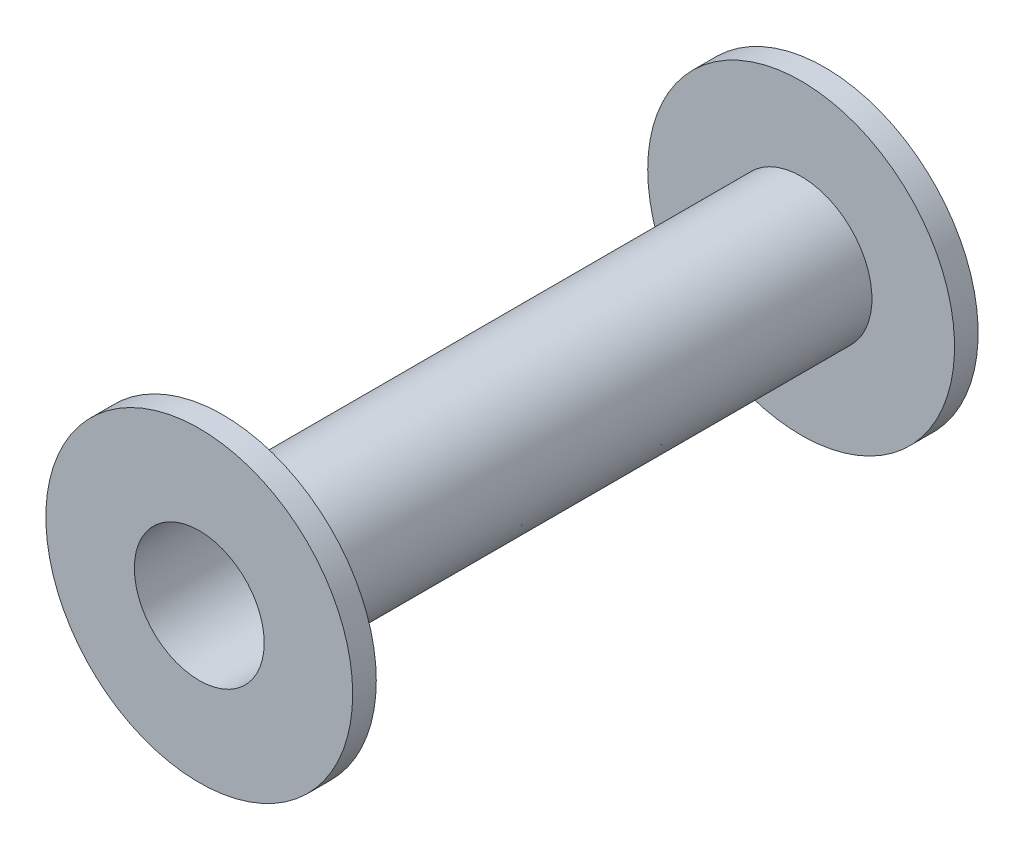
SolidWorks part; units mm, degrees
ref_plane "Front Plane" through (0, 0, 0) normal (0, 0, 1) x (1, 0, 0)
ref_plane "Top Plane" through (0, 0, 0) normal (0, 1, 0) x (1, 0, 0)
ref_plane "Right Plane" through (0, 0, 0) normal (1, 0, 0) x (0, 0, -1)
sketch "Sketch1" plane through (0, 0, 0) normal (0, 0, 1) x (1, 0, 0)
  circle A0 centre (0, 0) radius 5.5
  circle A1 centre (0, 0) radius 6
  dimension "D1" = 11
  dimension "D2" = 12
extrude "Extrude1" add sketch "Sketch1" along normal blind 49
sketch "Sketch2" plane through (0, 0, 49) normal (0, 0, 1) x (1, 0, 0)
  circle A0 centre (0, 0) radius 5.5
  circle A1 centre (0, 0) radius 13
  dimension "D1" = 26
  dimension "D2" = 11
extrude "Extrude3" add sketch "Sketch2" along normal blind 2
sketch "Sketch3" plane through (0, 0, 0) normal (0, 0, -1) x (-1, 0, 0)
  circle A0 centre (0, 0) radius 5.5
  circle A1 centre (0, 0) radius 13
  dimension "D1" = 11
  dimension "D2" = 26
extrude "Extrude4" add sketch "Sketch3" along normal blind 2
